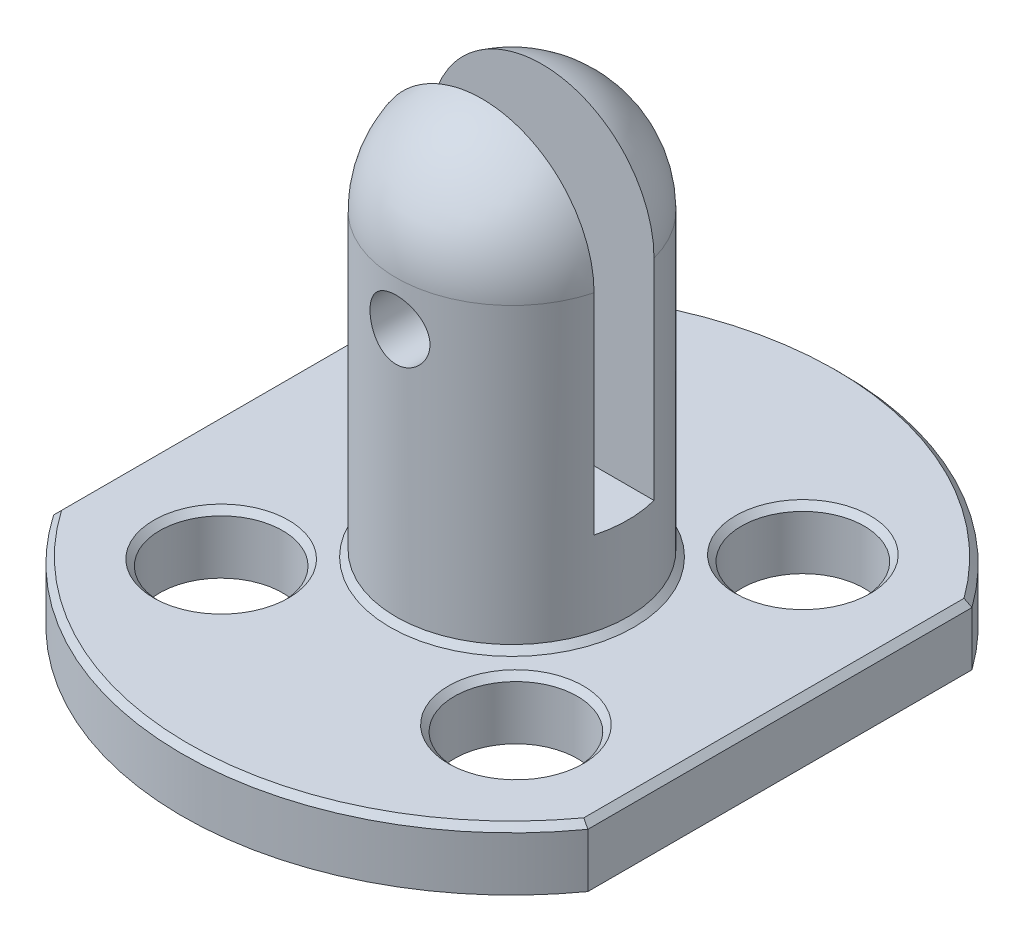
SolidWorks part; units mm, degrees
ref_plane "Front Plane" through (0, 0, 0) normal (0, 0, 1) x (1, 0, 0)
ref_plane "Top Plane" through (0, 0, 0) normal (0, 1, 0) x (1, 0, 0)
ref_plane "Right Plane" through (0, 0, 0) normal (1, 0, 0) x (0, 0, -1)
sketch "Sketch1" plane through (0, 0, 0) normal (0, 1, 0) x (1, 0, 0)
  line L0 (-9.0601, 6.2381) -> (-9.0601, -6.2381)
  line L1 (8.9399, 6.4093) -> (8.9399, -6.4093)
  arc A0 (-9.0601, -6.2381) -> (8.9399, -6.4093) centre (0, 0) ccw
  circle A2 centre (-4.918, 4.7881) radius 2.05
  circle A3 centre (4.7881, 4.918) radius 2.05
  circle A4 centre (4.918, -4.7881) radius 2.05
  circle A5 centre (-4.7881, -4.918) radius 2.05
  arc A6 (8.9399, 6.4093) -> (-9.0601, 6.2381) centre (0, 0) ccw
  point P14 (0, 0)
  point P16 (0, 0)
  point P17 (0, 0)
  dimension "D1" = 22
  dimension "D2" = 4.1
  dimension "D4" = 18
  dimension "D3" = 4
extrude "Boss-Extrude1" add sketch "Sketch1" along normal blind 2
sketch "Sketch2" plane through (0, 2, 0) normal (0, 1, 0) x (1, 0, 0)
  circle A0 centre (0, 0) radius 3.87
  dimension "D1" = 7.74
extrude "Boss-Extrude2" add sketch "Sketch2" along normal blind 10
sketch "Sketch3" plane through (0, 0, 0) normal (0, 0, 1) x (1, 0, 0)
  line L0 (3.87, 12) -> (-3.87, 12) construction
  line L1 (3.87, 2) -> (3.87, 12) construction
  line L2 (0, 15.87) -> (0, 12)
  line L3 (0, 12) -> (3.87, 12)
  arc A0 (3.87, 12) -> (0, 15.87) centre (0, 12) ccw
revolve "Revolve1" add sketch "Sketch3" angle 360 about L2
sketch "Sketch4" plane through (0, 0, 0) normal (0, -1, 0) x (1, 0, 0)
  circle A0 centre (0, 0) radius 3
  dimension "D1" = 6
extrude "Boss-Extrude3" add sketch "Sketch4" along normal blind 1 contours A0
ref_plane "Plane1" through (0, 20, 0) normal (0, 1, 0) x (1, 0, 0)
sketch "Sketch7" plane through (0, 20, 0) normal (0, 1, 0) x (1, 0, 0)
  line L0 (-7.3325, 0) -> (7.5791, 0) construction
  line L1 (-7.3325, 1) -> (7.5791, 1)
  line L2 (-7.3325, -1) -> (7.5791, -1)
  arc A0 (-7.3325, 1) -> (-7.3325, -1) centre (-7.3325, 0) ccw
  arc A1 (7.5791, -1) -> (7.5791, 1) centre (7.5791, 0) ccw
  point P3 (0.1233, 0)
  dimension "D1" = 2
extrude "Cut-Extrude2" cut sketch "Sketch7" against normal blind 15
sketch "Sketch9" plane through (0, 0, 0) normal (0, 0, 1) x (1, 0, 0)
  circle A0 centre (0, 10.5) radius 1
  dimension "D1" = 2
  dimension "D2" = 10.5
extrude "Cut-Extrude3" cut sketch "Sketch9" against normal through all both and the other way through all
chamfer "Chamfer1" distance 0.2 angle 45 9 edges at (-4.7881, 2, 6.968) (4.7881, 2, -2.868) (8.9399, 2, 0) (-0.1046, 2, 10.9995) (-9.0601, 2, 0) (-0.1046, 2, -10.9995) (-4.918, 2, -2.7381) (4.918, 2, 6.8381) (0, 2, 3.87)
